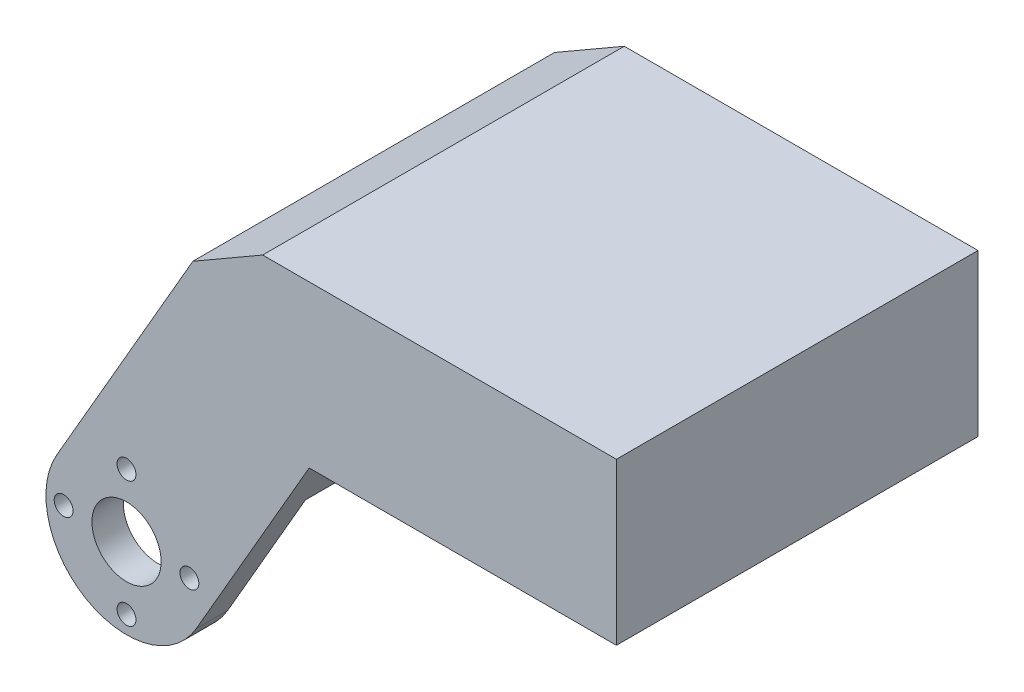
SolidWorks part; units mm, degrees
ref_plane "Front Plane" through (0, 0, 0) normal (0, 0, 1) x (1, 0, 0)
ref_plane "Top Plane" through (0, 0, 0) normal (0, 1, 0) x (1, 0, 0)
ref_plane "Right Plane" through (0, 0, 0) normal (1, 0, 0) x (0, 0, -1)
sketch "Sketch1" plane through (0, 0, 0) normal (0, 0, 1) x (1, 0, 0)
  line L0 (0, 0) -> (0, 30) construction
  line L1 (0, 30) -> (57.1438, 30) construction
  line L2 (0, 0) -> (17.3205, 30)
  line L3 (17.3205, 30) -> (0, 0) construction
  line L4 (26.1973, 24.875) -> (8.8768, -5.125)
  line L5 (8.4437, 35.125) -> (-8.8768, 5.125)
  line L6 (17.3205, 30) -> (62.3205, 30) construction
  line L7 (17.3205, 40.25) -> (62.3205, 40.25)
  line L8 (17.3205, 19.75) -> (62.3205, 19.75)
  line L9 (62.3205, 19.75) -> (62.3205, 40.25)
  line L10 (8.4437, 35.125) -> (17.3205, 40.25)
  circle A0 centre (0, 0) radius 10.25
  arc A1 (26.1973, 24.875) -> (8.4437, 35.125) centre (17.3205, 30) ccw
  arc A2 (-8.8768, 5.125) -> (8.8768, -5.125) centre (0, 0) ccw
  arc A3 (17.3205, 40.25) -> (17.3205, 19.75) centre (17.3205, 30) ccw
  arc A4 (62.3205, 19.75) -> (62.3205, 40.25) centre (62.3205, 30) ccw
  circle A5 centre (0, 0) radius 4.4
  circle A6 centre (0, 0) radius 8
  circle A7 centre (0, 8) radius 1.2
  circle A8 centre (8, 0) radius 1.2
  circle A9 centre (0, -8) radius 1.2
  circle A10 centre (-8, 0) radius 1.2
  point P3 (8.6603, 15)
  point P13 (39.8205, 30)
  point P36 (0, 0)
  dimension "D1" = 20.5
  dimension "D4" = 20.5
  dimension "D5" = 10.25
  dimension "D7" = 8.8
  dimension "D8" = 2.4
  dimension "D2" = 30
  dimension "D3" = 30
  dimension "D6" = 45
  dimension "D9" = 4
extrude "Boss-Extrude1" add sketch "Sketch1" against normal blind 46
sketch "Sketch4" plane through (-8.8768, 5.125, 0) normal (-0.866, 0.5, 0) x (0, 0, 1)
  line L0 (-46, -10.25) -> (0, -10.25) construction
  line L1 (-4, -10.25) -> (-42, -10.25)
  line L2 (-4, -10.25) -> (-4, 19.75)
  line L3 (-4, 19.75) -> (-42, 19.75)
  line L4 (-42, -10.25) -> (-42, 19.75)
  line L5 (-46, 34.641) -> (-46, 0) construction
  line L6 (0, 34.641) -> (0, 0) construction
  dimension "D1" = 4
  dimension "D2" = 4
  dimension "D3" = 30
extrude "Cut-Extrude1" cut sketch "Sketch4" against normal blind 46
